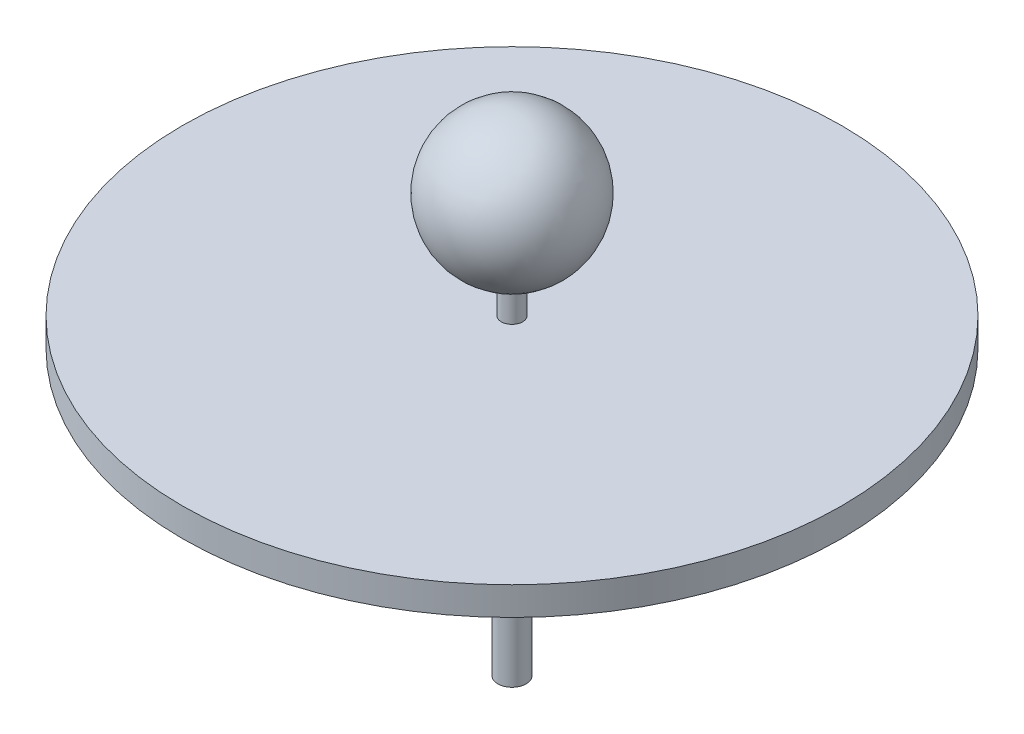
SolidWorks part; units mm, degrees
ref_plane "前视基准面" through (0, 0, 0) normal (0, 0, 1) x (1, 0, 0)
ref_plane "上视基准面" through (0, 0, 0) normal (0, 1, 0) x (1, 0, 0)
ref_plane "右视基准面" through (0, 0, 0) normal (1, 0, 0) x (0, 0, -1)
sketch "草图1" plane through (0, 0, 0) normal (0, 0, 1) x (1, 0, 0)
  line L0 (0, 0) -> (20, 0)
  line L1 (20, 0) -> (20, 100)
  line L2 (20, 100) -> (15, 100)
  line L3 (15, 100) -> (15, 200)
  line L4 (15, 200) -> (465, 200)
  line L5 (465, 200) -> (465, 240)
  line L6 (465, 240) -> (15, 240)
  line L7 (15, 240) -> (15, 290)
  line L8 (15, 290) -> (0, 290)
  line L9 (0, 290) -> (0, 0)
  line L10 (0, 290) -> (0, 390)
  line L11 (0, 390) -> (0, 491.1187)
  circle A0 centre (0, 390) radius 101.1187
  point P4 (0, 0)
revolve "旋转1" add sketch "草图1" angle 360 about L10
sketch "草图2" plane through (0, 0, 0) normal (0, -1, 0) x (1, 0, 0)
  circle A0 centre (0, 0) radius 20
extrude "凸台-拉伸1" add sketch "草图2" along normal blind 200
